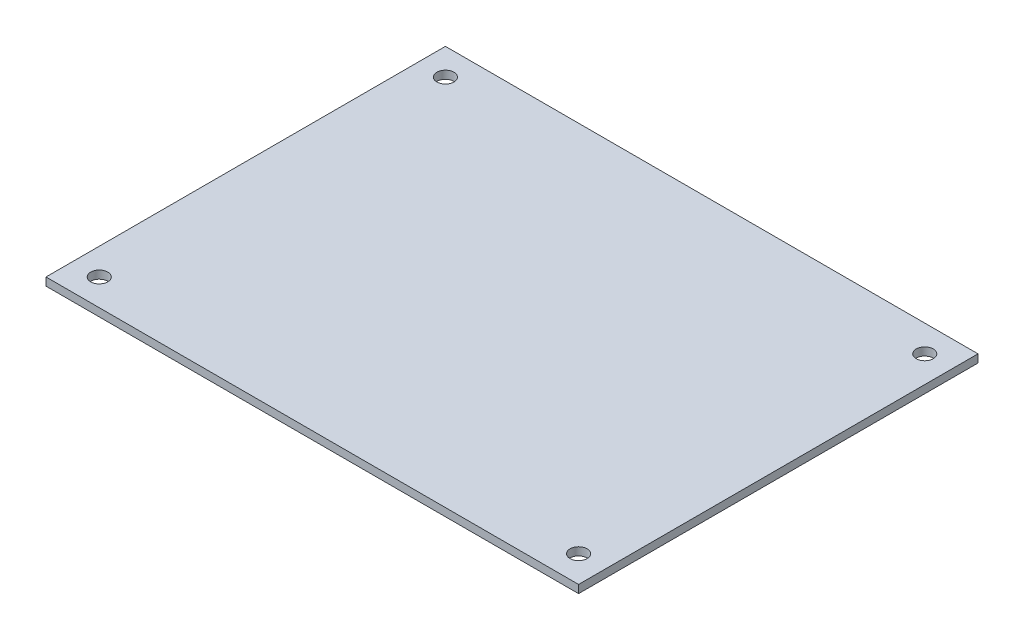
SolidWorks part; units mm, degrees
ref_plane "Front Plane" through (0, 0, 0) normal (0, 0, 1) x (1, 0, 0)
ref_plane "Top Plane" through (0, 0, 0) normal (0, 1, 0) x (1, 0, 0)
ref_plane "Right Plane" through (0, 0, 0) normal (1, 0, 0) x (0, 0, -1)
sketch "Sketch1" plane through (0, 0, 0) normal (0, 1, 0) x (1, 0, 0)
  line L0 (0, 37.5) -> (0, -37.5) construction
  line L1 (-50, -37.5) -> (50, -37.5)
  line L2 (-50, -37.5) -> (-50, 37.5)
  line L3 (-50, 37.5) -> (50, 37.5)
  line L4 (50, -37.5) -> (50, 37.5)
  line L5 (-50, -37.5) -> (50, 37.5) construction
  line L6 (-50, 37.5) -> (50, -37.5) construction
  line L7 (-50, 0) -> (50, 0) construction
  circle A0 centre (-45, 32.5) radius 1.6
  circle A1 centre (45, 32.5) radius 1.6
  circle A2 centre (45, -32.5) radius 1.6
  circle A3 centre (-45, -32.5) radius 1.6
  point P0 (0, 0)
  dimension "D3" = 3.2
  dimension "D1" = 75
  dimension "D2" = 100
  dimension "D4" = 5
  dimension "D5" = 5
extrude "Boss-Extrude1" add sketch "Sketch1" along normal blind 1.5
